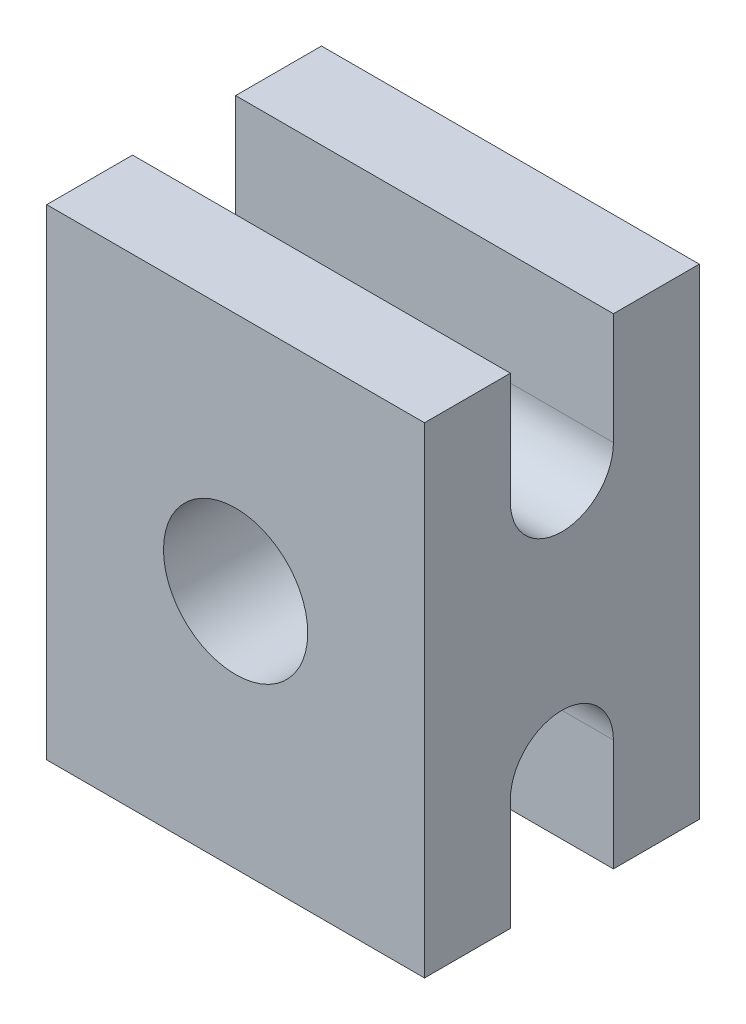
SolidWorks part; units mm, degrees
ref_plane "Спереди" through (0, 0, 0) normal (0, 0, 1) x (1, 0, 0)
ref_plane "Сверху" through (0, 0, 0) normal (0, 1, 0) x (1, 0, 0)
ref_plane "Справа" through (0, 0, 0) normal (1, 0, 0) x (0, 0, -1)
sketch "Эскиз1" plane through (0, 0, 0) normal (0, 0, 1) x (1, 0, 0)
  line L0 (0, 14) -> (11, 0) construction
  line L1 (0, 0) -> (11, 0)
  line L2 (0, 0) -> (0, 14)
  line L3 (0, 14) -> (11, 14)
  line L4 (11, 0) -> (11, 14)
  circle A0 centre (5.5, 7) radius 2.1
  dimension "D1" = 14
  dimension "D2" = 11
extrude "Вытянуть1" add sketch "Эскиз1" along normal blind 8
sketch "Эскиз2" plane through (11, 0, 0) normal (1, 0, 0) x (0, 0, -1)
  line L0 (-8, 0) -> (-8, 14) construction
  line L1 (-5.5, 15.2427) -> (-2.5, 15.2427)
  line L2 (-5.5, 15.2427) -> (-5.5, 10.75)
  line L3 (-5.5, -1.9656) -> (-2.5, -1.9656)
  line L4 (-2.5, 15.2427) -> (-2.5, 10.75)
  line L5 (-2.5, 3.25) -> (-2.5, -1.9656)
  line L6 (-5.5, 3.25) -> (-5.5, -1.9656)
  line L7 (-8, 14) -> (0, 14) construction
  arc A0 (-5.5, 10.75) -> (-2.5, 10.75) centre (-4, 10.75) ccw
  arc A1 (-5.5, 3.25) -> (-2.5, 3.25) centre (-4, 3.25) cw
  dimension "D3" = 1.5
  dimension "D4" = 1.5
  dimension "D5" = 7.5
  dimension "D6" = 3.25
  dimension "D1" = 3
  dimension "D2" = 2.5
extrude "Вырез-Вытянуть1" cut sketch "Эскиз2" against normal blind 18
